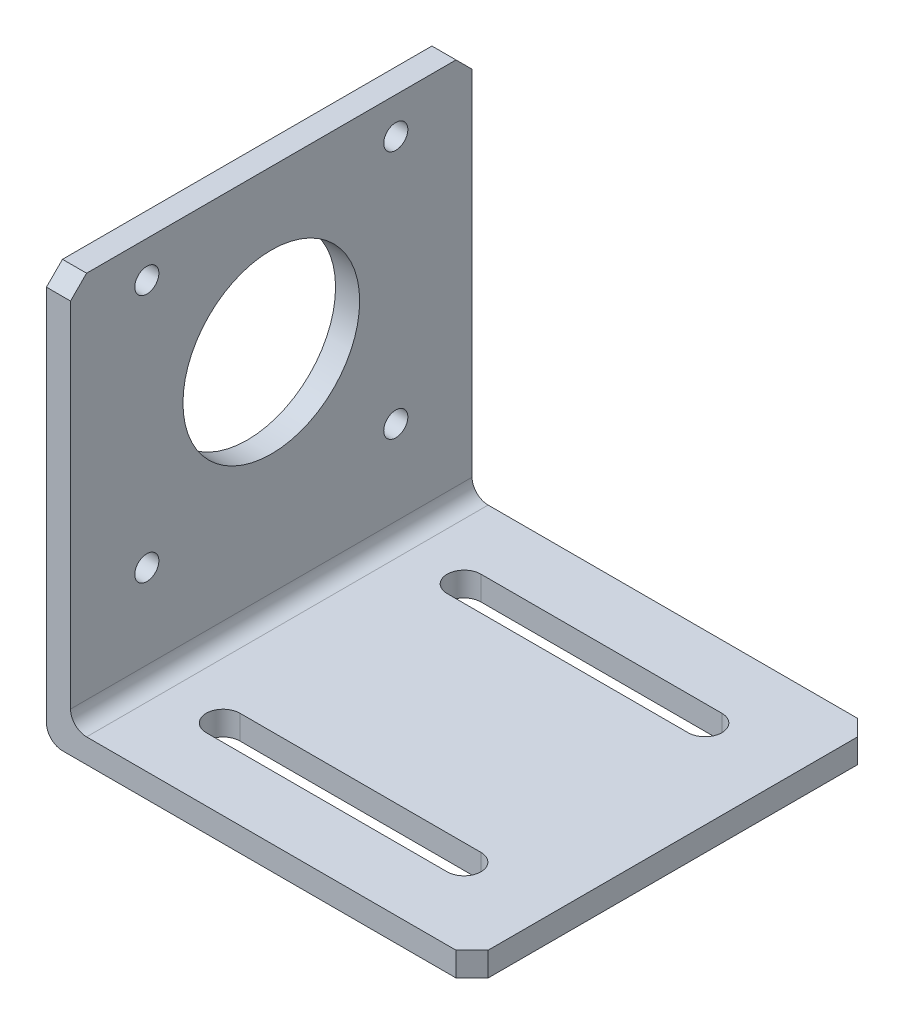
SolidWorks part; units mm, degrees
ref_plane "Ön Düzlem" through (0, 0, 0) normal (0, 0, 1) x (1, 0, 0)
ref_plane "Üst Düzlem" through (0, 0, 0) normal (0, 1, 0) x (1, 0, 0)
ref_plane "Sağ Düzlem" through (0, 0, 0) normal (1, 0, 0) x (0, 0, -1)
sketch "Çizim1" plane through (0, 0, 0) normal (0, 0, 1) x (1, 0, 0)
  line L0 (0, 51) -> (0, 2)
  line L1 (2, 0) -> (53, 0)
  line L2 (53, 0) -> (53, 3)
  line L3 (53, 3) -> (5, 3)
  line L4 (3, 5) -> (3, 51)
  line L5 (3, 51) -> (0, 51)
  arc A0 (5, 3) -> (3, 5) centre (5, 5) cw
  arc A1 (0, 2) -> (2, 0) centre (2, 2) ccw
  point P11 (0, 0)
  dimension "D2" = 2
  dimension "D5" = 2
  dimension "D1" = 3
  dimension "D3" = 51
  dimension "D4" = 53
extrude "Yükseklik-Ekstrüzyon1" add sketch "Çizim1" along normal blind 50
sketch "Çizim2" plane through (3, 0, 0) normal (1, 0, 0) x (0, 0, -1)
  line L0 (-25, 31) -> (-25, 51) construction
  line L1 (-9.5, 15.5) -> (-40.5, 15.5) construction
  line L2 (-9.5, 15.5) -> (-9.5, 46.5) construction
  line L3 (-9.5, 46.5) -> (-40.5, 46.5) construction
  line L4 (-40.5, 15.5) -> (-40.5, 46.5) construction
  line L5 (-9.5, 15.5) -> (-40.5, 46.5) construction
  line L6 (-9.5, 46.5) -> (-40.5, 15.5) construction
  line L7 (-50, 51) -> (0, 51) construction
  circle A1 centre (-25, 31) radius 11
  circle A2 centre (-9.5, 46.5) radius 1.5
  circle A3 centre (-40.5, 46.5) radius 1.5
  circle A6 centre (-9.5, 15.5) radius 1.5
  circle A7 centre (-40.5, 15.5) radius 1.5
  dimension "D1" = 20
  dimension "D2" = 22
  dimension "D6" = 3
  dimension "D3" = 31
extrude "Kes-Ekstrüzyon1" cut sketch "Çizim2" against normal through all contours A3 | A1 | A2 | A7 | A6
sketch "Çizim3" plane through (0, 3, 0) normal (0, 1, 0) x (1, 0, 0)
  line L0 (53, -50) -> (5, -50) construction
  line L1 (53, -50) -> (53, 0) construction
  line L3 (42, -12.1) -> (12, -12.1)
  line L4 (42, -7.9) -> (12, -7.9)
  line L6 (42, -37.9) -> (12, -37.9)
  line L7 (42, -42.1) -> (12, -42.1)
  arc A0 (42, -12.1) -> (42, -7.9) centre (42, -10) ccw
  arc A1 (12, -7.9) -> (12, -12.1) centre (12, -10) ccw
  arc A2 (12, -42.1) -> (12, -37.9) centre (12, -40) cw
  arc A3 (42, -37.9) -> (42, -42.1) centre (42, -40) cw
  dimension "D3" = 4.2
  dimension "D1" = 30
  dimension "D2" = 7.9
  dimension "D4" = 30
  dimension "D5" = 11
extrude "Kes-Ekstrüzyon2" cut sketch "Çizim3" against normal blind 10 and the other way through all contours L6 A2 L7 A3 | A0 L4 A1 L3
sketch "Çizim4" plane through (3, 0, 0) normal (1, 0, 0) x (0, 0, -1)
  line L0 (-50, 49) -> (-50, 51)
  line L1 (-50, 49) -> (-48, 51)
  line L3 (-50, 51) -> (-48, 51)
  line L5 (0, 49) -> (0, 51)
  line L6 (0, 49) -> (-2, 51)
  line L7 (0, 51) -> (-2, 51)
  point P0 (-50, 51)
  dimension "D1" = 2
extrude "Kes-Ekstrüzyon3" cut sketch "Çizim4" against normal through all contours L7 L6 L5 | L3 L1 L0
sketch "Çizim5" plane through (0, 3, 0) normal (0, 1, 0) x (1, 0, 0)
  line L4 (53, -48) -> (51, -50)
  line L5 (51, -50) -> (53, -50)
  line L6 (53, -50) -> (53, -48)
  line L7 (53, 0) -> (53, -2)
  line L8 (51, 0) -> (53, 0)
  line L9 (53, -2) -> (51, 0)
  point P0 (53, -50)
  point P12 (53, 0)
  dimension "D1" = 2
extrude "Kes-Ekstrüzyon4" cut sketch "Çizim5" against normal through all contours L5 L6 L4 | L7 L9 L8
